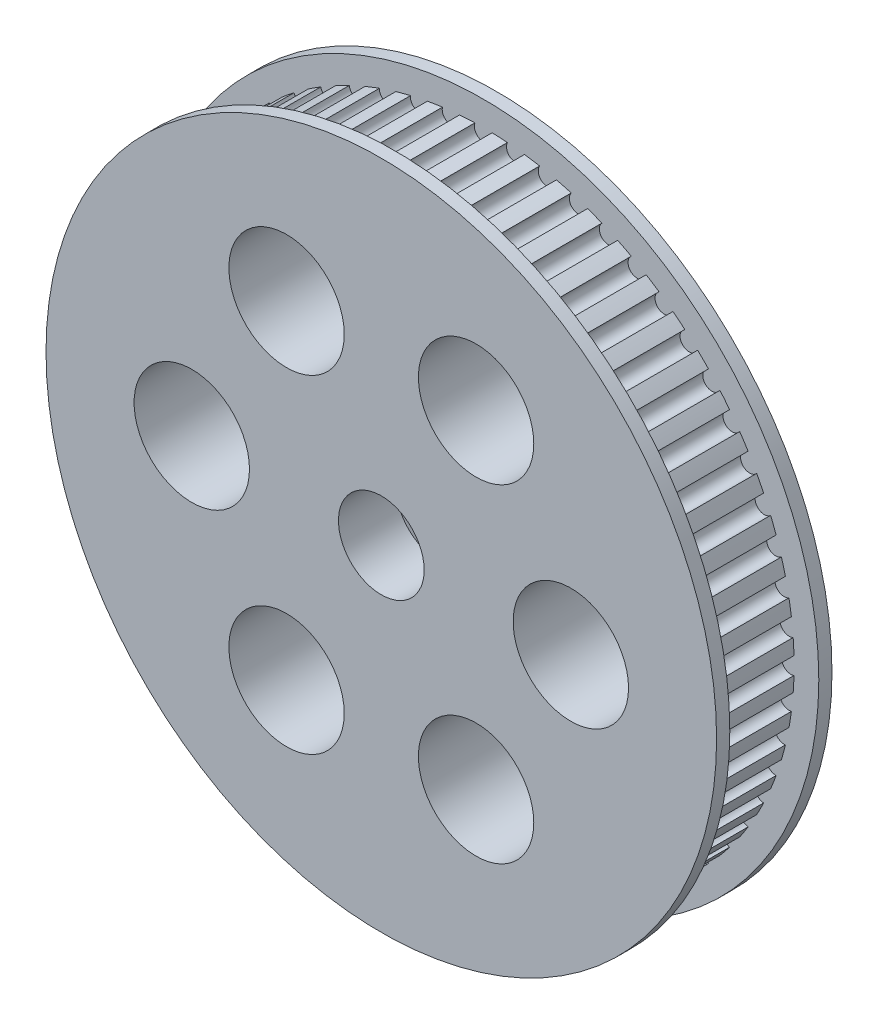
SolidWorks part; units mm, degrees
ref_plane "Front Plane" through (0, 0, 0) normal (0, 0, 1) x (1, 0, 0)
ref_plane "Top Plane" through (0, 0, 0) normal (0, 1, 0) x (1, 0, 0)
ref_plane "Right Plane" through (0, 0, 0) normal (1, 0, 0) x (0, 0, -1)
ref_plane "Plane1" through (0, 0, 334) normal (0, 0, 1) x (1, 0, 0)
sketch "Sketch1" plane through (0, 0, 334) normal (0, 0, 1) x (1, 0, 0)
  circle A0 centre (300, 170) radius 4.5
  circle A1 centre (300, 170) radius 2.6
extrude "Boss-Extrude1" add sketch "Sketch1" along normal blind 7.5
ref_plane "Plane2" through (0, 0, 334.5) normal (0, 0, 1) x (1, 0, 0)
sketch "Sketch2" plane through (0, 0, 334.5) normal (0, 0, 1) x (1, 0, 0)
  circle A0 centre (300, 170) radius 20.3446
  circle A1 centre (300, 170) radius 4.5
extrude "Boss-Extrude2" add sketch "Sketch2" along normal blind 0.8
ref_plane "Plane3" through (0, 0, 340.7) normal (0, 0, 1) x (1, 0, 0)
sketch "Sketch3" plane through (0, 0, 340.7) normal (0, 0, 1) x (1, 0, 0)
  circle A0 centre (300, 170) radius 20.3446
  circle A1 centre (300, 170) radius 4.5
extrude "Boss-Extrude3" add sketch "Sketch3" along normal blind 0.8
ref_plane "Plane4" through (0, 0, 335.3) normal (0, 0, 1) x (1, 0, 0)
sketch "Sketch4" plane through (0, 0, 335.3) normal (0, 0, 1) x (1, 0, 0)
  circle A0 centre (300, 170) radius 18.8446
  circle A1 centre (300, 170) radius 4.5
extrude "Boss-Extrude4" add sketch "Sketch4" along normal blind 5.4
sketch "Sketch5" plane through (0, 0, 335.3) normal (0, 0, 1) x (1, 0, 0)
  circle A0 centre (318.6496, 170) radius 0.555
  circle A1 centre (318.5474, 171.9494) radius 0.555
  circle A2 centre (318.2421, 173.8775) radius 0.555
  circle A3 centre (317.7368, 175.763) radius 0.555
  circle A4 centre (317.0373, 177.5855) radius 0.555
  circle A5 centre (316.151, 179.3248) radius 0.555
  circle A6 centre (315.0878, 180.962) radius 0.555
  circle A7 centre (313.8593, 182.479) radius 0.555
  circle A8 centre (312.479, 183.8593) radius 0.555
  circle A9 centre (310.962, 185.0878) radius 0.555
  circle A10 centre (309.3248, 186.151) radius 0.555
  circle A11 centre (307.5855, 187.0373) radius 0.555
  circle A12 centre (305.763, 187.7368) radius 0.555
  circle A13 centre (303.8775, 188.2421) radius 0.555
  circle A14 centre (301.9494, 188.5474) radius 0.555
  circle A15 centre (300, 188.6496) radius 0.555
  circle A16 centre (298.0506, 188.5474) radius 0.555
  circle A17 centre (296.1225, 188.2421) radius 0.555
  circle A18 centre (294.237, 187.7368) radius 0.555
  circle A19 centre (292.4145, 187.0373) radius 0.555
  circle A20 centre (290.6752, 186.151) radius 0.555
  circle A21 centre (289.038, 185.0878) radius 0.555
  circle A22 centre (287.521, 183.8593) radius 0.555
  circle A23 centre (286.1407, 182.479) radius 0.555
  circle A24 centre (284.9122, 180.962) radius 0.555
  circle A25 centre (283.849, 179.3248) radius 0.555
  circle A26 centre (282.9627, 177.5855) radius 0.555
  circle A27 centre (282.2632, 175.763) radius 0.555
  circle A28 centre (281.7579, 173.8775) radius 0.555
  circle A29 centre (281.4526, 171.9494) radius 0.555
  circle A30 centre (281.3504, 170) radius 0.555
  circle A31 centre (281.4526, 168.0506) radius 0.555
  circle A32 centre (281.7579, 166.1225) radius 0.555
  circle A33 centre (282.2632, 164.237) radius 0.555
  circle A34 centre (282.9627, 162.4145) radius 0.555
  circle A35 centre (283.849, 160.6752) radius 0.555
  circle A36 centre (284.9122, 159.038) radius 0.555
  circle A37 centre (286.1407, 157.521) radius 0.555
  circle A38 centre (287.521, 156.1407) radius 0.555
  circle A39 centre (289.038, 154.9122) radius 0.555
  circle A40 centre (290.6752, 153.849) radius 0.555
  circle A41 centre (292.4145, 152.9627) radius 0.555
  circle A42 centre (294.237, 152.2632) radius 0.555
  circle A43 centre (296.1225, 151.7579) radius 0.555
  circle A44 centre (298.0506, 151.4526) radius 0.555
  circle A45 centre (300, 151.3504) radius 0.555
  circle A46 centre (301.9494, 151.4526) radius 0.555
  circle A47 centre (303.8775, 151.7579) radius 0.555
  circle A48 centre (305.763, 152.2632) radius 0.555
  circle A49 centre (307.5855, 152.9627) radius 0.555
  circle A50 centre (309.3248, 153.849) radius 0.555
  circle A51 centre (310.962, 154.9122) radius 0.555
  circle A52 centre (312.479, 156.1407) radius 0.555
  circle A53 centre (313.8593, 157.521) radius 0.555
  circle A54 centre (315.0878, 159.038) radius 0.555
  circle A55 centre (316.151, 160.6752) radius 0.555
  circle A56 centre (317.0373, 162.4145) radius 0.555
  circle A57 centre (317.7368, 164.237) radius 0.555
  circle A58 centre (318.2421, 166.1225) radius 0.555
  circle A59 centre (318.5474, 168.0506) radius 0.555
extrude "Cut-Extrude1" cut sketch "Sketch5" along normal blind 5.4
sketch "Sketch6" plane through (0, 0, 334) normal (0, 0, 1) x (1, 0, 0)
  line L0 (304.7343, 170) -> (302.3671, 174.1)
  line L1 (302.3671, 174.1) -> (297.6329, 174.1)
  line L2 (297.6329, 174.1) -> (295.2657, 170)
  line L3 (295.2657, 170) -> (297.6329, 165.9)
  line L4 (297.6329, 165.9) -> (302.3671, 165.9)
  line L5 (302.3671, 165.9) -> (304.7343, 170)
extrude "Cut-Extrude2" cut sketch "Sketch6" along normal blind 4
sketch "Sketch7" plane through (0, 0, 334) normal (0, 0, 1) x (1, 0, 0)
  circle A0 centre (311.5, 170) radius 3.5
  circle A1 centre (305.75, 179.9593) radius 3.5
  circle A2 centre (294.25, 179.9593) radius 3.5
  circle A3 centre (288.5, 170) radius 3.5
  circle A4 centre (294.25, 160.0407) radius 3.5
  circle A5 centre (305.75, 160.0407) radius 3.5
extrude "Cut-Extrude3" cut sketch "Sketch7" along normal blind 8
